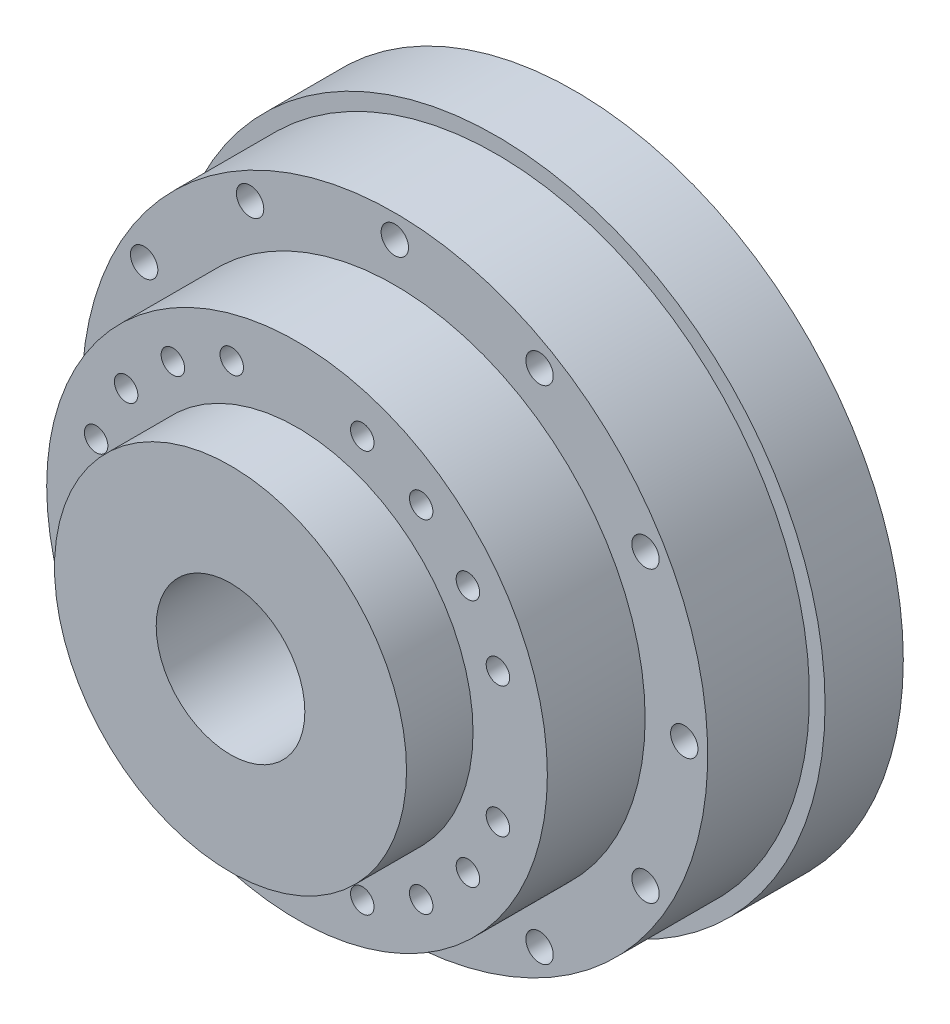
SolidWorks part; units mm, degrees
ref_plane "Спереди" through (0, 0, 0) normal (0, 0, 1) x (1, 0, 0)
ref_plane "Сверху" through (0, 0, 0) normal (0, 1, 0) x (1, 0, 0)
ref_plane "Справа" through (0, 0, 0) normal (1, 0, 0) x (0, 0, -1)
other "Configuration Table"
sketch "Эскиз1" plane through (0, 0, 0) normal (0, 0, 1) x (1, 0, 0)
  circle A0 centre (0, 0) radius 42
  dimension "D1" = 84
extrude "Бобышка-Вытянуть1" add sketch "Эскиз1" along normal blind 10
sketch "Эскиз2" plane through (0, 0, 10) normal (0, 0, 1) x (1, 0, 0)
  circle A0 centre (0, 0) radius 40
  dimension "D1" = 80
extrude "Бобышка-Вытянуть2" add sketch "Эскиз2" along normal blind 13
sketch "Эскиз3" plane through (0, 0, 23) normal (0, 0, 1) x (1, 0, 0)
  circle A0 centre (0, 0) radius 32
  dimension "D1" = 64
extrude "Бобышка-Вытянуть3" add sketch "Эскиз3" along normal blind 12.5
sketch "Эскиз4" plane through (0, 0, 35.5) normal (0, 0, 1) x (1, 0, 0)
  circle A0 centre (0, 0) radius 22.5
  dimension "D1" = 45
extrude "Бобышка-Вытянуть4" add sketch "Эскиз4" along normal blind 8.5
sketch "Эскиз5" plane through (0, 0, 0) normal (0, 0, -1) x (-1, 0, 0)
  circle A0 centre (0, 0) radius 22.5
  dimension "D1" = 45
extrude "Бобышка-Вытянуть5" add sketch "Эскиз5" along normal blind 5.5
sketch "Эскиз6" plane through (0, 0, -5.5) normal (0, 0, -1) x (-1, 0, 0)
  circle A0 centre (0, 0) radius 12.5
  dimension "D1" = 25
extrude "Бобышка-Вытянуть6" add sketch "Эскиз6" along normal blind 7
sketch "Эскиз7" plane through (0, 0, -12.5) normal (0, 0, -1) x (-1, 0, 0)
  circle A0 centre (0, 0) radius 9.5
  dimension "D1" = 19
extrude "Вырез-Вытянуть1" cut sketch "Эскиз7" against normal up to surface (56.5 mm away) up to face at (22.5, 0, 44)
sketch "Эскиз8" plane through (0, 0, 23) normal (0, 0, 1) x (1, 0, 0)
  circle A0 centre (0, 37) radius 1.75
  circle A1 centre (18.5, 32.0429) radius 1.75
  circle A2 centre (32.0429, 18.5) radius 1.75
  circle A3 centre (37, 0) radius 1.75
  circle A4 centre (32.0429, -18.5) radius 1.75
  circle A5 centre (18.5, -32.0429) radius 1.75
  circle A6 centre (0, -37) radius 1.75
  circle A7 centre (-18.5, -32.0429) radius 1.75
  circle A8 centre (-32.0429, -18.5) radius 1.75
  circle A9 centre (-37, 0) radius 1.75
  circle A10 centre (-32.0429, 18.5) radius 1.75
  circle A11 centre (-18.5, 32.0429) radius 1.75
  point P19 (0, 0)
  dimension "D2" = 3.5
  dimension "D1" = 37
  dimension "D3" = 12
extrude "Вырез-Вытянуть2" cut sketch "Эскиз8" against normal up to surface (23 mm away) up to face at (-22.5, 0, 0)
sketch "Эскиз9" plane through (0, 0, 35.5) normal (0, 0, 1) x (1, 0, 0)
  line L0 (-8.3435, 25.6785) -> (0, 0) construction
  line L1 (0, 0) -> (0, 19.5382) construction
  circle A0 centre (-8.3435, 25.6785) radius 1.5
  circle A2 centre (8.3435, 25.6785) radius 1.5
  circle A3 centre (15.8702, 21.8435) radius 1.5
  circle A4 centre (21.8435, 15.8702) radius 1.5
  circle A5 centre (25.6785, 8.3435) radius 1.5
  circle A7 centre (25.6785, -8.3435) radius 1.5
  circle A8 centre (21.8435, -15.8702) radius 1.5
  circle A9 centre (15.8702, -21.8435) radius 1.5
  circle A10 centre (8.3435, -25.6785) radius 1.5
  circle A12 centre (-8.3435, -25.6785) radius 1.5
  circle A13 centre (-15.8702, -21.8435) radius 1.5
  circle A14 centre (-21.8435, -15.8702) radius 1.5
  circle A15 centre (-25.6785, -8.3435) radius 1.5
  circle A17 centre (-25.6785, 8.3435) radius 1.5
  circle A18 centre (-21.8435, 15.8702) radius 1.5
  circle A19 centre (-15.8702, 21.8435) radius 1.5
  circle A20 centre (0, 27) radius 1.5 [skipped]
  circle A21 centre (27, 0) radius 1.5 [skipped]
  circle A22 centre (0, -27) radius 1.5 [skipped]
  circle A23 centre (-27, 0) radius 1.5 [skipped]
  point P27 (0, 0)
  dimension "D1" = 3
  dimension "D2" = 27
  dimension "D4" = 18
  dimension "D3" = 20
extrude "Вырез-Вытянуть3" cut sketch "Эскиз9" against normal blind 10
ref_plane "Плоскость1" through (0, 12.5, 0) normal (0, 1, 0) x (1, 0, 0)
sketch "Эскиз11" plane through (0, 12.5, 0) normal (0, 1, 0) x (1, 0, 0)
  line L0 (12.5, 12.5) -> (-12.5, 12.5) construction
  circle A0 centre (0, 10) radius 1.5
  point P2 (0, 0)
  dimension "D1" = 3
  dimension "D2" = 2.5
extrude "Вырез-Вытянуть4" cut sketch "Эскиз11" against normal up to surface (3 mm away)
pattern_circular "Круговой массив1" count 3 over 360 about axis through (0, 0, 70.8701) along (0, 0, -1) of "Вырез-Вытянуть4"
